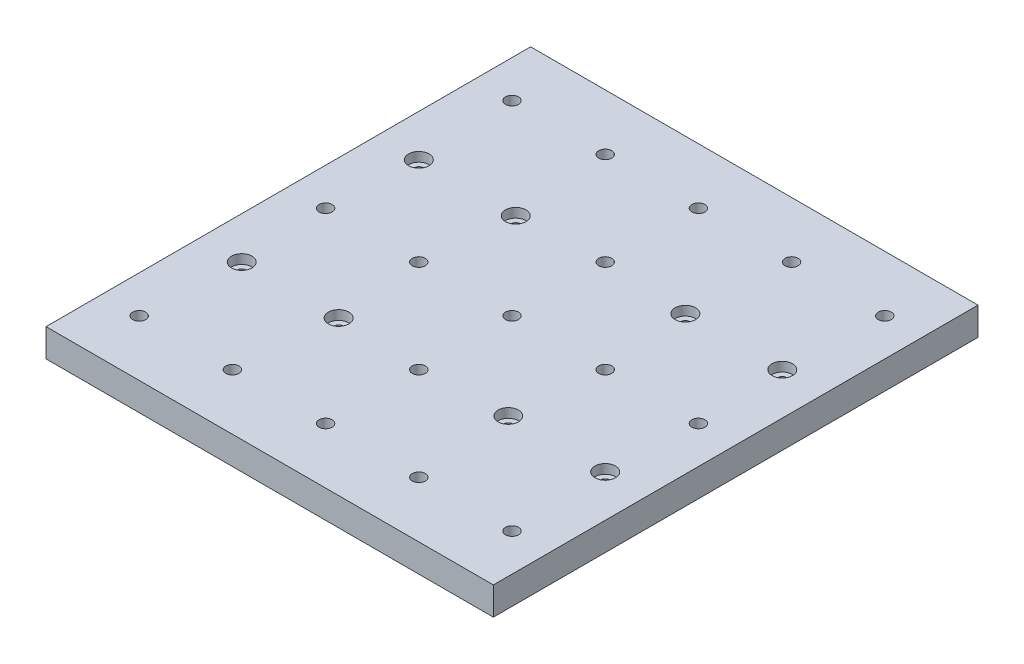
SolidWorks part; units mm, degrees
material "Haya"
ref_plane "Alzado" through (0, 0, 0) normal (0, 0, 1) x (1, 0, 0)
ref_plane "Planta" through (0, 0, 0) normal (0, 1, 0) x (1, 0, 0)
ref_plane "Vista lateral" through (0, 0, 0) normal (1, 0, 0) x (0, 0, -1)
sketch "Croquis1" plane through (0, 0, 0) normal (0, 1, 0) x (1, 0, 0)
  line L1 (-120, -130) -> (120, -130)
  line L2 (-120, -130) -> (-120, 130)
  line L3 (-120, 130) -> (120, 130)
  line L4 (120, -130) -> (120, 130)
  line L5 (-120, -130) -> (120, 130) construction
  line L6 (-120, 130) -> (120, -130) construction
  point P0 (0, 0)
  dimension "D1" = 240
  dimension "D2" = 260
extrude "Saliente-Extruir1" add sketch "Croquis1" along normal blind 15
sketch "Croquis2" plane through (0, 15, 0) normal (0, 1, 0) x (1, 0, 0)
  line L0 (-120, 0) -> (120, 0) construction
  line L1 (-120, 130) -> (-120, -130) construction
  line L2 (120, -130) -> (120, 130) construction
  line L3 (0, 130) -> (0, -130) construction
  line L4 (120, 130) -> (-120, 130) construction
  line L5 (-120, -130) -> (120, -130) construction
  line L6 (-105.5, -47.5) -> (-37.5, -47.5) construction
  line L13 (-105.5, -30) -> (-37.5, -30) construction
  line L14 (-105.5, -30) -> (-105.5, -65) construction
  line L15 (-105.5, -65) -> (-37.5, -65) construction
  line L16 (-37.5, -30) -> (-37.5, -65) construction
  line L17 (-105.5, -30) -> (-37.5, -65) construction
  line L18 (-105.5, -65) -> (-37.5, -30) construction
  circle A4 centre (-44.5, -47.5) radius 2.55
  circle A5 centre (-98.5, -47.5) radius 2.55
  circle A6 centre (98.5, -47.5) radius 2.55
  circle A7 centre (44.5, -47.5) radius 2.55
  circle A8 centre (-44.5, 47.5) radius 2.55
  circle A9 centre (-98.5, 47.5) radius 2.55
  circle A10 centre (98.5, 47.5) radius 2.55
  circle A11 centre (44.5, 47.5) radius 2.55
  point P17 (-71.5, -47.5)
  dimension "D6" = 5.1
  dimension "D1" = 65
  dimension "D2" = 68
  dimension "D3" = 35
  dimension "D4" = 48.5
  dimension "D5" = 7
  dimension "D7" = 7
sketch "Croquis6" plane through (0, 0, 0) normal (0, -1, 0) x (1, 0, 0)
  circle A0 centre (-45.5, -47.5) radius 2.55
  circle A1 centre (-97.5, -47.5) radius 2.55
  circle A2 centre (-97.5, 47.5) radius 2.55
  circle A3 centre (-45.5, 47.5) radius 2.55
  circle A4 centre (45.5, 47.5) radius 2.55
  circle A5 centre (97.5, 47.5) radius 2.55
  circle A6 centre (45.5, -47.5) radius 2.55
  circle A7 centre (97.5, -47.5) radius 2.55
  dimension "D1" = 5.1
extrude "Cortar-Extruir3" cut sketch "Croquis6" against normal through all
sketch "Croquis7" plane through (0, 15, 0) normal (0, 1, 0) x (1, 0, 0)
  circle A0 centre (-97.5, 47.5) radius 5.5
  circle A1 centre (-45.5, 47.5) radius 5.5
  circle A2 centre (-97.5, -47.5) radius 5.5
  circle A3 centre (-45.5, -47.5) radius 5.5
  circle A4 centre (45.5, -47.5) radius 5.5
  circle A5 centre (97.5, -47.5) radius 5.5
  circle A6 centre (97.5, 47.5) radius 5.5
  circle A7 centre (45.5, 47.5) radius 5.5
  dimension "D1" = 11
extrude "Cortar-Extruir4" cut sketch "Croquis7" against normal blind 5
sketch "Croquis8" plane through (0, 15, 0) normal (0, 1, 0) x (1, 0, 0)
  line L0 (-120, 130) -> (-120, -130) construction
  line L1 (120, 130) -> (-120, 130) construction
  circle A0 centre (-100, 100) radius 3.5
  circle A1 centre (-50, 100) radius 3.5
  circle A2 centre (0, 100) radius 3.5
  circle A3 centre (50, 100) radius 3.5
  circle A4 centre (100, 100) radius 3.5
  circle A5 centre (-50, 50) radius 3.5 construction
  circle A6 centre (0, 50) radius 3.5
  circle A7 centre (50, 50) radius 3.5 construction
  circle A8 centre (100, 50) radius 3.5 construction
  circle A9 centre (-50, 0) radius 3.5
  circle A10 centre (0, 0) radius 3.5
  circle A11 centre (50, 0) radius 3.5
  circle A12 centre (100, 0) radius 3.5
  circle A13 centre (-50, -50) radius 3.5 construction
  circle A14 centre (0, -50) radius 3.5
  circle A15 centre (50, -50) radius 3.5 construction
  circle A16 centre (100, -50) radius 3.5 construction
  circle A17 centre (-50, -100) radius 3.5
  circle A18 centre (0, -100) radius 3.5
  circle A19 centre (50, -100) radius 3.5
  circle A20 centre (100, -100) radius 3.5
  circle A21 centre (-100, 50) radius 3.5 construction
  circle A22 centre (-100, 0) radius 3.5
  circle A23 centre (-100, -50) radius 3.5 construction
  circle A24 centre (-100, -100) radius 3.5
  dimension "D3" = 7
  dimension "D6" = 50
  dimension "D1" = 20
  dimension "D2" = 30
  dimension "D7" = 50
  dimension "D4" = 5
  dimension "D5" = 5
extrude "Cortar-Extruir5" cut sketch "Croquis8" against normal through all
